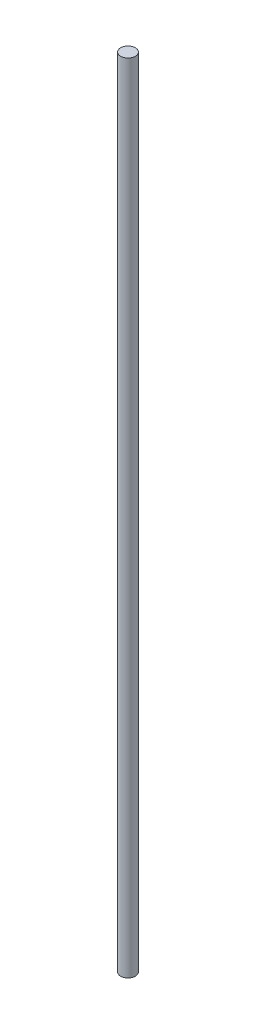
SolidWorks part; units mm, degrees
ref_plane "前视基准面" through (0, 0, 0) normal (0, 0, 1) x (1, 0, 0)
ref_plane "上视基准面" through (0, 0, 0) normal (0, 1, 0) x (1, 0, 0)
ref_plane "右视基准面" through (0, 0, 0) normal (1, 0, 0) x (0, 0, -1)
other "Configuration Table"
sketch "草图1" plane through (0, 0, 0) normal (0, 1, 0) x (1, 0, 0)
  circle A0 centre (0, 0) radius 4
  dimension "D1" = 8
extrude "凸台-拉伸1" add sketch "草图1" along normal blind 432
